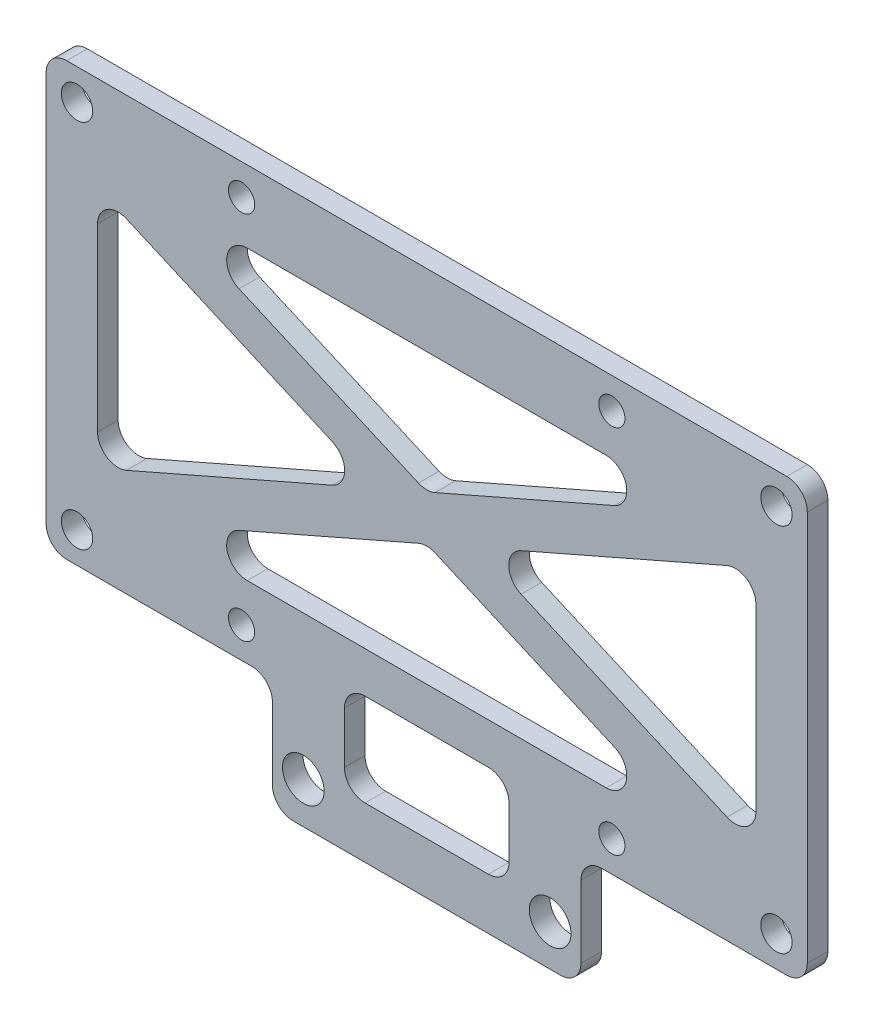
SolidWorks part; units mm, degrees
material "A-玻璃纤维"
ref_plane "前视基准面" through (0, 0, 0) normal (0, 0, 1) x (1, 0, 0)
ref_plane "上视基准面" through (0, 0, 0) normal (0, 1, 0) x (1, 0, 0)
ref_plane "右视基准面" through (0, 0, 0) normal (1, 0, 0) x (0, 0, -1)
other "Configuration Table"
sketch "草图1" plane through (0, 0, 0) normal (0, 0, 1) x (1, 0, 0)
  line L1 (-37, -21) -> (37, -21)
  line L2 (-37, -21) -> (-37, 21)
  line L3 (-37, 21) -> (37, 21)
  line L4 (37, -21) -> (37, 21)
  line L5 (-37, -21) -> (37, 21) construction
  line L6 (-37, 21) -> (37, -21) construction
  line L7 (-30, -18) -> (30, -18) construction
  line L8 (-30, -18) -> (-30, 18) construction
  line L9 (-30, 18) -> (30, 18) construction
  line L10 (30, -18) -> (30, 18) construction
  line L11 (-30, -18) -> (30, 18) construction
  line L12 (-30, 18) -> (30, -18) construction
  line L13 (-18, -18) -> (18, -18) construction
  line L14 (-18, -18) -> (-18, 18) construction
  line L15 (-18, 18) -> (18, 18) construction
  line L16 (18, -18) -> (18, 18) construction
  line L17 (-18, -18) -> (18, 18) construction
  line L18 (-18, 18) -> (18, -18) construction
  circle A0 centre (18, 18) radius 1.275
  circle A1 centre (-18, 18) radius 1.275
  circle A2 centre (-18, -18) radius 1.275
  circle A3 centre (18, -18) radius 1.275
  point P0 (0, 0)
  point P6 (0, 0)
  point P11 (0, 0)
  dimension "D5" = 2.55
  dimension "D1" = 74
  dimension "D2" = 36
  dimension "D3" = 60
  dimension "D4" = 3
extrude "凸台-拉伸1" add sketch "草图1" along normal blind 2
sketch "草图2" plane through (0, 0, 2) normal (0, 0, 1) x (1, 0, 0)
  line L0 (37, -21) -> (37, 21) construction
  line L1 (-34, -18) -> (34, -18) construction
  line L2 (-34, -18) -> (-34, 18) construction
  line L3 (-34, 18) -> (34, 18) construction
  line L4 (34, -18) -> (34, 18) construction
  line L5 (-34, -18) -> (34, 18) construction
  line L6 (-34, 18) -> (34, -18) construction
  line L7 (37, 21) -> (-37, 21) construction
  circle A0 centre (34, 18) radius 1.525
  circle A1 centre (-34, 18) radius 1.525
  circle A2 centre (-34, -18) radius 1.525
  circle A3 centre (34, -18) radius 1.525
  point P0 (0, 0)
  dimension "D3" = 3.05
  dimension "D1" = 3
  dimension "D2" = 3
extrude "切除-拉伸1" cut sketch "草图2" against normal blind 2
fillet "圆角1" radius 2 4 edges at (37, -21, 1) (-37, -21, 1) (-37, 21, 1) (37, 21, 1)
sketch "草图3" plane through (0, 0, 2) normal (0, 0, 1) x (1, 0, 0)
  line L0 (-35, -21) -> (35, -21) construction
  line L1 (-15, -32) -> (15, -32)
  line L2 (-15, -32) -> (-15, -10)
  line L3 (-15, -10) -> (15, -10)
  line L4 (15, -32) -> (15, -10)
  line L5 (-15, -32) -> (15, -10) construction
  line L6 (-15, -10) -> (15, -32) construction
  point P0 (0, -21)
  dimension "D1" = 30
  dimension "D2" = 11
extrude "凸台-拉伸2" add sketch "草图3" against normal up to surface (2 mm away) up to face at (35.525, -18, 0)
sketch "草图4" plane through (0, 0, 2) normal (0, 0, 1) x (1, 0, 0)
  line L0 (-12, -28) -> (12, -28) construction
  line L1 (0, 0) -> (0, -28) construction
  circle A0 centre (12, -28) radius 2.025 construction
  circle A2 centre (12, -28) radius 2.025
  circle A3 centre (-12, -28) radius 2.025
extrude "切除-拉伸2" cut sketch "草图4" against normal blind 10
fillet "圆角2" radius 2 4 edges at (15, -32, 1) (15, -21, 1) (-15, -21, 1) (-15, -32, 1)
sketch "草图5" plane through (0, 0, 0) normal (0, 0, -1) x (-1, 0, 0)
  line L0 (37, 19) -> (37, -19) construction
  line L1 (-32, -14) -> (32, -14)
  line L2 (-32, -14) -> (-32, 14)
  line L3 (-32, 14) -> (32, 14)
  line L4 (32, -14) -> (32, 14)
  line L5 (-32, -14) -> (32, 14) construction
  line L6 (-32, 14) -> (32, -14) construction
  line L7 (-32.8016, 12.1677) -> (31.1984, -15.8323)
  line L8 (-31.1984, -15.8323) -> (32.8016, 12.1677)
  line L9 (-31.1984, 15.8323) -> (32.8016, -12.1677)
  line L10 (-32.8016, -12.1677) -> (31.1984, 15.8323)
  circle A0 centre (34, 18) radius 1.525 construction
  arc A1 (-32.8016, 12.1677) -> (-31.1984, 15.8323) centre (-32, 14) cw
  arc A2 (31.1984, -15.8323) -> (32.8016, -12.1677) centre (32, -14) ccw
  arc A3 (-31.1984, -15.8323) -> (-32.8016, -12.1677) centre (-32, -14) cw
  arc A4 (32.8016, 12.1677) -> (31.1984, 15.8323) centre (32, 14) ccw
  point P0 (0, 0)
  dimension "D1" = 4
  dimension "D2" = 5
  dimension "D3" = 2
  dimension "D4" = 2
extrude "切除-拉伸3" cut sketch "草图5" against normal blind 10 contours L8 L1 L7 | L2 L10 L7 | L9 L10 L3 | L8 L9 L4
sketch "草图6" plane through (0, 0, 0) normal (0, 0, -1) x (-1, 0, 0)
  line L0 (0, 0) -> (0, -22.5) construction
  line L1 (-8, -27) -> (8, -27)
  line L2 (-8, -27) -> (-8, -18)
  line L3 (-8, -18) -> (8, -18)
  line L4 (8, -27) -> (8, -18)
  line L5 (-8, -27) -> (8, -18) construction
  line L6 (-8, -18) -> (8, -27) construction
  line L7 (-27.0102, -14) -> (27.0102, -14) construction
  line L8 (13, -32) -> (-13, -32) construction
  circle A0 centre (12, -28) radius 2.025 construction
  point P0 (0, -22.5)
  dimension "D1" = 4
  dimension "D2" = 4
  dimension "D3" = 5
extrude "切除-拉伸4" cut sketch "草图6" against normal blind 10
fillet "圆角3" radius 2 16 edges at (32, 11.817, 1) (4.9898, 0, 1) (32, -11.817, 1) (0, -2.183, 1) (-27.0102, -14, 1) (27.0102, -14, 1) (-32, 11.817, 1) (-32, -11.817, 1) (-4.9898, 0, 1) (-27.0102, 14, 1) (0, 2.183, 1) (27.0102, 14, 1) (8, -27, 1) (-8, -27, 1) (-8, -18, 1) (8, -18, 1)
